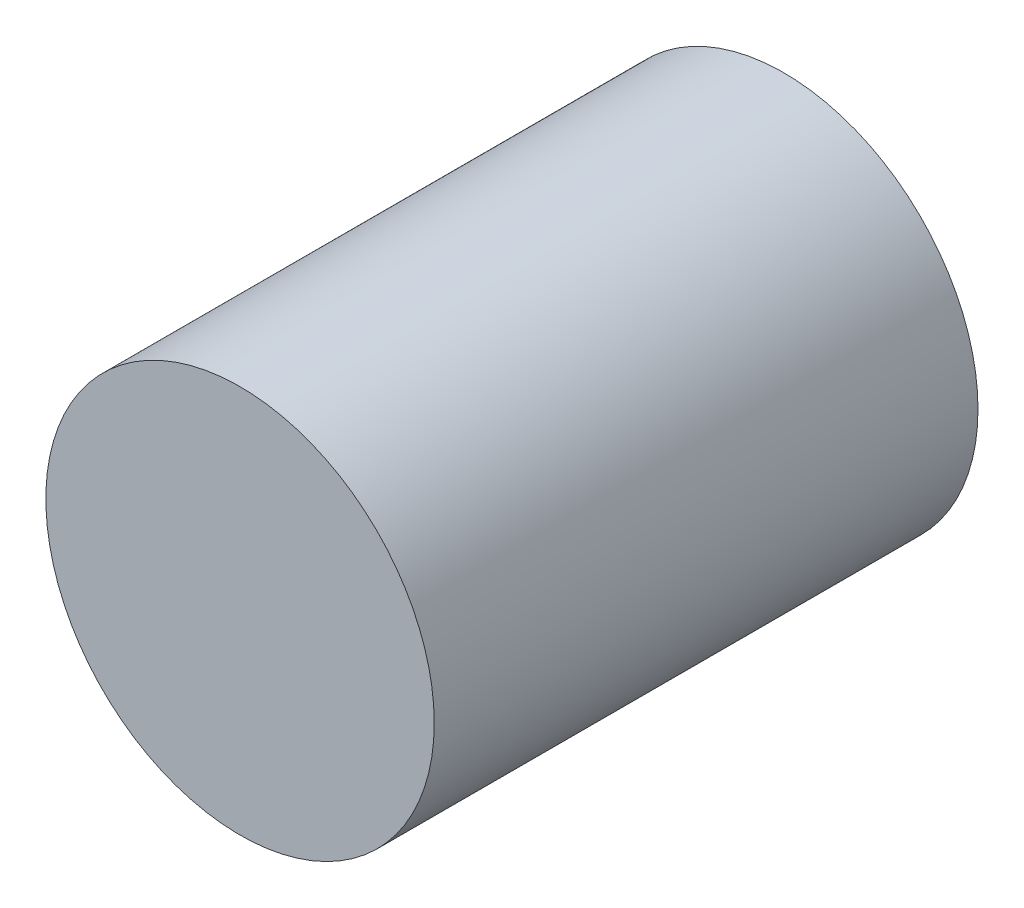
SolidWorks part; units mm, degrees
material "Malleable Cast Iron"
ref_plane "Front Plane" through (0, 0, 0) normal (0, 0, 1) x (1, 0, 0)
ref_plane "Top Plane" through (0, 0, 0) normal (0, 1, 0) x (1, 0, 0)
ref_plane "Right Plane" through (0, 0, 0) normal (1, 0, 0) x (0, 0, -1)
sketch "Sketch1" plane through (0, 0, 0) normal (0, 0, 1) x (1, 0, 0)
  circle A0 centre (0, 0) radius 5
  dimension "D1" = 10
extrude "Boss-Extrude1" add sketch "Sketch1" along normal blind 14
